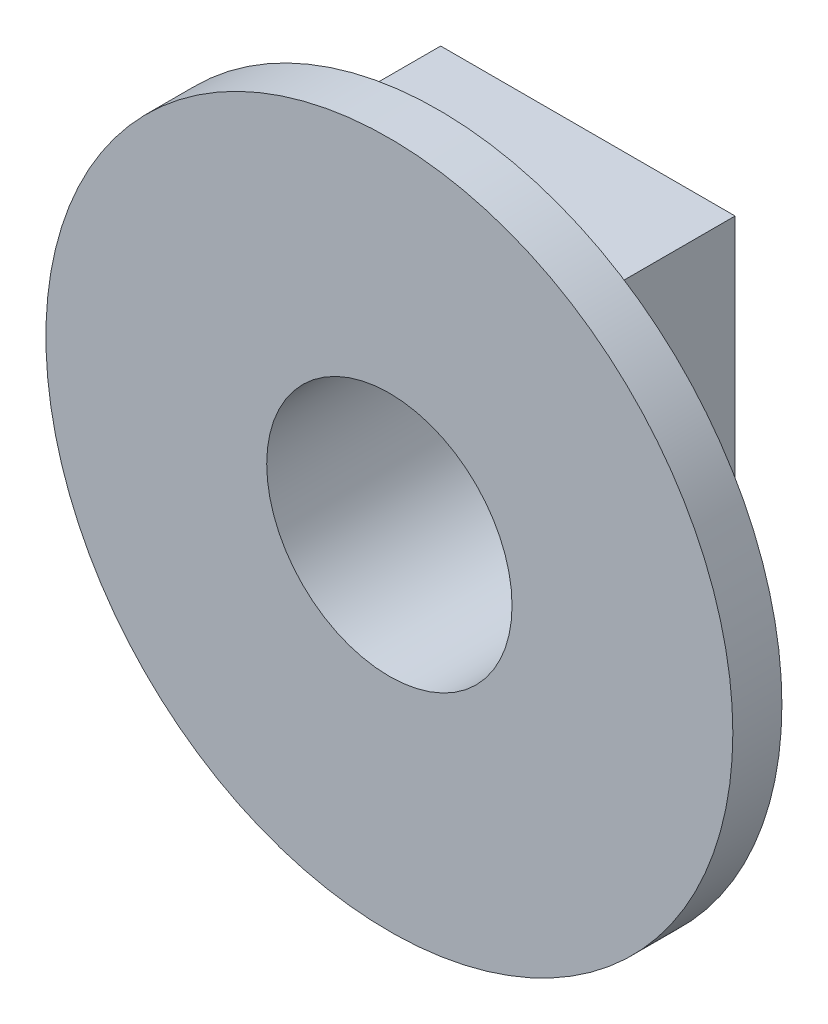
SolidWorks part; units mm, degrees
ref_plane "Front Plane" through (0, 0, 0) normal (0, 0, 1) x (1, 0, 0)
ref_plane "Top Plane" through (0, 0, 0) normal (0, 1, 0) x (1, 0, 0)
ref_plane "Right Plane" through (0, 0, 0) normal (1, 0, 0) x (0, 0, -1)
sketch "Sketch1" plane through (0, 0, 0) normal (0, 0, 1) x (1, 0, 0)
  circle A0 centre (-7.3458, 32.1021) radius 7
  dimension "D1" = 14
extrude "Boss-Extrude1" add sketch "Sketch1" along normal blind 1
ref_plane "Plane1" through (-7.3, 0, 0) normal (1, 0, 0) x (0, 0, -1)
sketch "Sketch3" plane through (-7.3, 0, 0) normal (1, 0, 0) x (0, 0, -1)
  line L1 (3, 27.2506) -> (0, 27.2506)
  line L2 (3, 27.2506) -> (3, 37.2506)
  line L3 (3, 37.2506) -> (0, 37.2506)
  line L4 (0, 27.2506) -> (0, 37.2506)
  line L5 (3, 27.2506) -> (0, 37.2506) construction
  line L6 (3, 37.2506) -> (0, 27.2506) construction
  line L7 (0, 25.1021) -> (0, 39.1021) construction
  point P0 (1.5, 32.2506)
  dimension "D1" = 0
  dimension "D2" = 10
  dimension "D3" = 3
sketch "Sketch4" plane through (0, 0, 0) normal (0, 0, -1) x (-1, 0, 0)
  line L0 (7.3, 32.2506) -> (14.3442, 32.2506)
  line L1 (7.3, 37.2506) -> (7.3, 27.2506) construction
  circle A0 centre (7.3458, 32.1021) radius 7 construction
extrude "Boss-Extrude2" add sketch "Sketch3" along normal mid plane 6
sketch "Sketch5" plane through (0, 0, 1) normal (0, 0, 1) x (1, 0, 0)
  circle A0 centre (-7.3458, 32.1021) radius 2.5
  circle A1 centre (-7.3458, 32.1021) radius 7 construction
  dimension "D1" = 5
extrude "Cut-Extrude1" cut sketch "Sketch5" against normal blind 5
